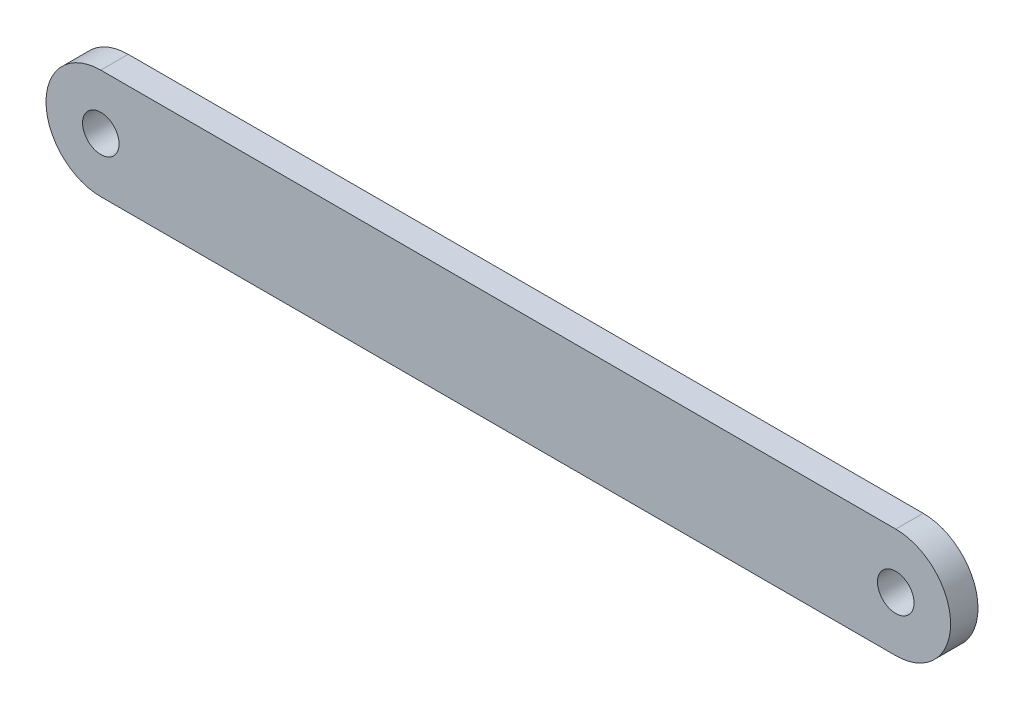
SolidWorks part; units mm, degrees
ref_plane "Front Plane" through (0, 0, 0) normal (0, 0, 1) x (1, 0, 0)
ref_plane "Top Plane" through (0, 0, 0) normal (0, 1, 0) x (1, 0, 0)
ref_plane "Right Plane" through (0, 0, 0) normal (1, 0, 0) x (0, 0, -1)
sketch "Sketch1" plane through (0, 0, 0) normal (0, 0, 1) x (1, 0, 0)
  line L0 (-35.3127, 0) -> (51.6873, 0) construction
  line L1 (-35.3127, 6) -> (51.6873, 6)
  line L2 (-35.3127, -6) -> (51.6873, -6)
  arc A0 (-35.3127, 6) -> (-35.3127, -6) centre (-35.3127, 0) ccw
  arc A1 (51.6873, -6) -> (51.6873, 6) centre (51.6873, 0) ccw
  circle A2 centre (-35.3127, 0) radius 2
  circle A3 centre (51.6873, 0) radius 2
  point P3 (8.1873, 0)
  dimension "D3" = 4
  dimension "D4" = 4
  dimension "D1" = 87
  dimension "D2" = 12
extrude "Boss-Extrude3" add sketch "Sketch1" along normal blind 3
